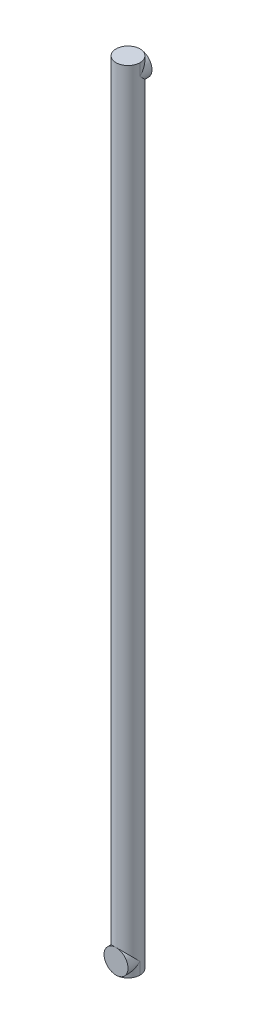
SolidWorks part; units mm, degrees
material "기본"
ref_plane "정면" through (0, 0, 0) normal (0, 0, 1) x (1, 0, 0)
ref_plane "윗면" through (0, 0, 0) normal (0, 1, 0) x (1, 0, 0)
ref_plane "우측면" through (0, 0, 0) normal (1, 0, 0) x (0, 0, -1)
sketch "스케치2" plane through (0, 0, 0) normal (0, 1, 0) x (1, 0, 0)
  circle A0 centre (0, 0) radius 2.5
extrude "보스-돌출1" add sketch "스케치2" along normal blind 165
sketch "스케치3" plane through (0, 0, 0) normal (0, 0, 1) x (1, 0, 0)
  circle A0 centre (0, 2.5) radius 2.5
  dimension "D1" = 2.5
extrude "보스-돌출2" add sketch "스케치3" along normal blind 2.5
sketch "스케치4" plane through (0, 0, 0) normal (0, 0, 1) x (1, 0, 0)
  line L0 (2.5, 165) -> (-2.5, 165) construction
  circle A0 centre (0, 162.5) radius 2.5
  dimension "D1" = 2.5
extrude "보스-돌출3" add sketch "스케치4" against normal blind 2.5
sketch "스케치5" plane through (0, 0, 0) normal (0, 0, 1) x (1, 0, 0)
  point P0 (0, 2.5)
